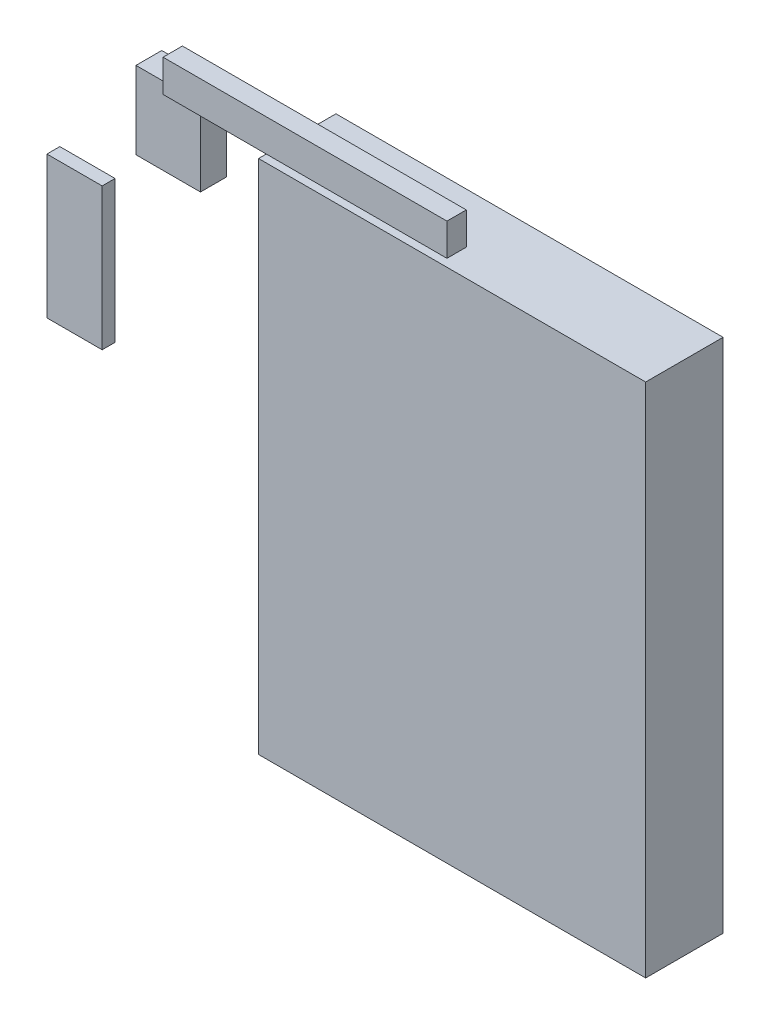
SolidWorks part; units mm, degrees
ref_plane "前基準面" through (0, 0, 0) normal (0, 0, 1) x (1, 0, 0)
ref_plane "上基準面" through (0, 0, 0) normal (0, 1, 0) x (1, 0, 0)
ref_plane "右基準面" through (0, 0, 0) normal (1, 0, 0) x (0, 0, -1)
sketch "草圖1" plane through (0, 0, 0) normal (0, 0, 1) x (1, 0, 0)
  line L0 (19, 24) -> (49, 24)
  line L1 (49, 24) -> (49, 64)
  line L2 (49, 64) -> (19, 64)
  line L3 (19, 64) -> (19, 24)
extrude "battery pouch" add sketch "草圖1" along normal blind 6 from offset 3.6
sketch "草圖2" plane through (0, 0, 0) normal (0, 0, 1) x (1, 0, 0)
  line L0 (12, 65) -> (34, 65)
  line L1 (34, 65) -> (34, 67.5)
  line L2 (34, 67.5) -> (12, 67.5)
  line L3 (12, 67.5) -> (12, 65)
extrude "battery leads" add sketch "草圖2" along normal blind 1.5 from offset 8.5
sketch "草圖3" plane through (0, 0, 0) normal (0, 0, 1) x (1, 0, 0)
  line L0 (9.5, 59.5) -> (14.5, 59.5)
  line L1 (14.5, 59.5) -> (14.5, 65.5)
  line L2 (14.5, 65.5) -> (9.5, 65.5)
  line L3 (9.5, 65.5) -> (9.5, 59.5)
extrude "JST plug wire exit below J4" add sketch "草圖3" along normal blind 2 from offset 7.6
sketch "草圖4" plane through (0, 0, 0) normal (0, 0, 1) x (1, 0, 0)
  line L0 (-4, 38.5) -> (0.28, 38.5)
  line L1 (0.28, 38.5) -> (0.28, 49.5)
  line L2 (0.28, 49.5) -> (-4, 49.5)
  line L3 (-4, 49.5) -> (-4, 38.5)
extrude "microSD card, part outside the connector" add sketch "草圖4" along normal blind 1 from offset 2
